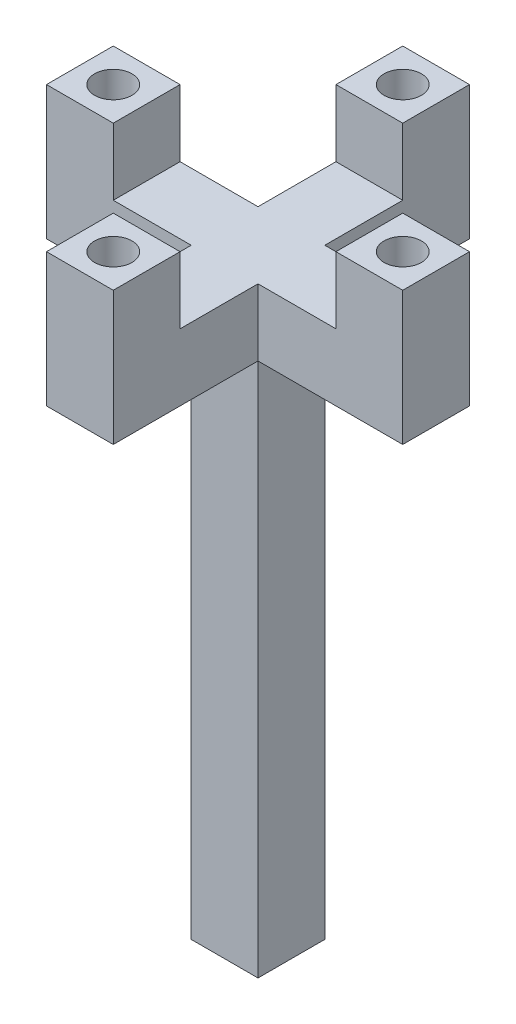
SolidWorks part; units mm, degrees
ref_plane "Front Plane" through (0, 0, 0) normal (0, 0, 1) x (1, 0, 0)
ref_plane "Top Plane" through (0, 0, 0) normal (0, 1, 0) x (1, 0, 0)
ref_plane "Right Plane" through (0, 0, 0) normal (1, 0, 0) x (0, 0, -1)
sketch "Sketch1" plane through (0, 0, 0) normal (0, 0, 1) x (1, 0, 0)
  line L0 (12.5, 75) -> (20, 75)
  line L2 (3.75, 60) -> (3.75, 0)
  line L3 (3.75, 0) -> (-3.75, 0)
  line L5 (0, 0) -> (0, 67.5) construction
  line L7 (-12.5, 75) -> (-20, 75)
  line L9 (-3.75, 60) -> (-3.75, 0)
  line L11 (-20, 75) -> (-20, 60)
  line L12 (-20, 60) -> (-3.75, 60)
  line L13 (20, 75) -> (20, 60)
  line L14 (20, 60) -> (3.75, 60)
  line L15 (12.5, 75) -> (12.5, 67.5)
  line L16 (12.5, 67.5) -> (0, 67.5)
  line L17 (0, 67.5) -> (-12.5, 67.5)
  line L18 (-12.5, 67.5) -> (-12.5, 75)
  point P14 (0, 0)
  dimension "D1" = 7.5
  dimension "D2" = 60
  dimension "D3" = 40
  dimension "D4" = 7.5
  dimension "D5" = 15
  dimension "D6" = 7.5
extrude "Boss-Extrude1" add sketch "Sketch1" along normal blind 7.5
sketch "Sketch3" plane through (0, 75, 0) normal (0, 1, 0) x (1, 0, 0)
  line L0 (-20, 0) -> (-12.5, -7.5) construction
  line L1 (-12.5, -7.5) -> (12.5, 0) construction
  line L2 (12.5, 0) -> (20, -7.5) construction
  circle A0 centre (-16.25, -3.75) radius 2.1
  circle A1 centre (16.25, -3.75) radius 2.1
  dimension "D1" = 4.2
  dimension "D2" = 32.5
extrude "Cut-Extrude1" cut sketch "Sketch3" against normal blind 5
pattern_circular "CirPattern1" count 2 every 90 about axis through (0, 0, 3.75) along (0, 1, 0) of bodies 102
combine bodies "Combine1" bodies to combine 102 103
